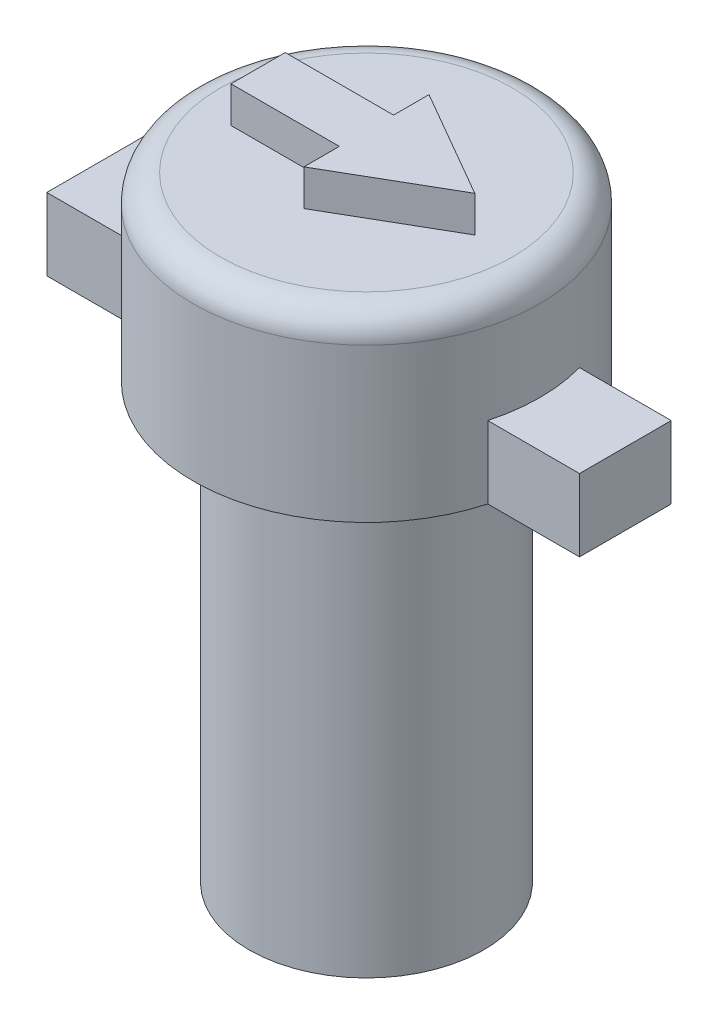
SolidWorks part; units mm, degrees
ref_plane "Front Plane" through (0, 0, 0) normal (0, 0, 1) x (1, 0, 0)
ref_plane "Top Plane" through (0, 0, 0) normal (0, 1, 0) x (1, 0, 0)
ref_plane "Right Plane" through (0, 0, 0) normal (1, 0, 0) x (0, 0, -1)
sketch "Sketch1" plane through (0, 0, 0) normal (0, 1, 0) x (1, 0, 0)
  circle A0 centre (0, 0) radius 3.25
  dimension "D1" = 6.5
extrude "Boss-Extrude1" add sketch "Sketch1" along normal blind 12.018 contours A0
sketch "Sketch2" plane through (0, 0, 0) normal (0, -1, 0) x (1, 0, 0)
  circle A1 centre (0, 0) radius 1.75
  dimension "D1" = 3.5
extrude "Cut-Extrude1" [suppressed] cut sketch "Sketch2" against normal blind 2.5
sketch "Sketch6" plane through (0, 12.018, 0) normal (0, 1, 0) x (1, 0, 0)
  circle A0 centre (0, 0) radius 4.8
  dimension "D1" = 9.6
extrude "Boss-Extrude2" add sketch "Sketch6" along normal blind 5 contours A0
fillet "Fillet1" radius 0.75 1 edges at (0, 17.018, 4.8)
sketch "Sketch7" plane through (0, 17.018, 0) normal (0, 1, 0) x (1, 0, 0)
  line L0 (0, 0) -> (-3, 0) construction
  line L1 (0, 0) -> (1, 0) construction
  line L2 (0, 0) -> (1, 0) construction
  line L3 (3, 0) -> (0, 1.7321)
  line L4 (0, 1.7321) -> (0, -1.7321)
  line L5 (0, -1.7321) -> (3, 0)
  line L6 (1, 0) -> (3, 0) construction
  line L7 (-3, 0) -> (-3, 0.75)
  line L8 (-3, 0.75) -> (0, 0.75)
  line L9 (0, 0.75) -> (0, -0.75)
  line L10 (0, -0.75) -> (-3, -0.75)
  line L11 (-3, -0.75) -> (-3, 0)
  circle A0 centre (1, 0) radius 1 construction
  dimension "D1" = 1
  dimension "D2" = 2
  dimension "D3" = 3
  dimension "D4" = 0.75
  dimension "D5" = 0.75
sketch "Sketch8" plane through (0, 17.018, 0) normal (0, 1, 0) x (1, 0, 0)
  line L0 (0, 0.75) -> (-3, 0.75)
  line L1 (-3, 0.75) -> (-3, -0.75)
  line L2 (-3, -0.75) -> (0, -0.75)
  line L3 (0, -0.75) -> (0, -1.7321)
  line L4 (0, -1.7321) -> (3, 0)
  line L5 (3, 0) -> (0, 1.7321)
  line L6 (0, 1.7321) -> (0, 0.75)
extrude "Boss-Extrude3" add sketch "Sketch8" along normal blind 1
sketch "Sketch9" plane through (0, 12.018, 0) normal (0, -1, 0) x (1, 0, 0)
  line L1 (-4.4058, 1.905) -> (-6.9458, 1.905)
  line L2 (-6.9458, 1.905) -> (-6.9458, -1.905)
  line L3 (-6.9458, -1.905) -> (-4.4058, -1.905)
  line L4 (4.6289, 1.27) -> (7.1689, 1.27)
  line L5 (7.1689, 1.27) -> (7.1689, -1.27)
  line L6 (7.1689, -1.27) -> (4.6289, -1.27)
  arc A0 (-4.4058, 1.905) -> (-4.4058, -1.905) centre (0, 0) ccw
  circle A1 centre (0, 0) radius 4.8
  arc A2 (4.6289, -1.27) -> (4.6289, 1.27) centre (0, 0) ccw
  point P11 (0, 0)
  dimension "D2" = 2.54
  dimension "D3" = 3.81
  dimension "D4" = 2.54
  dimension "D5" = 2.54
  dimension "D1" = 0
extrude "Boss-Extrude4" add sketch "Sketch9" against normal blind 2
